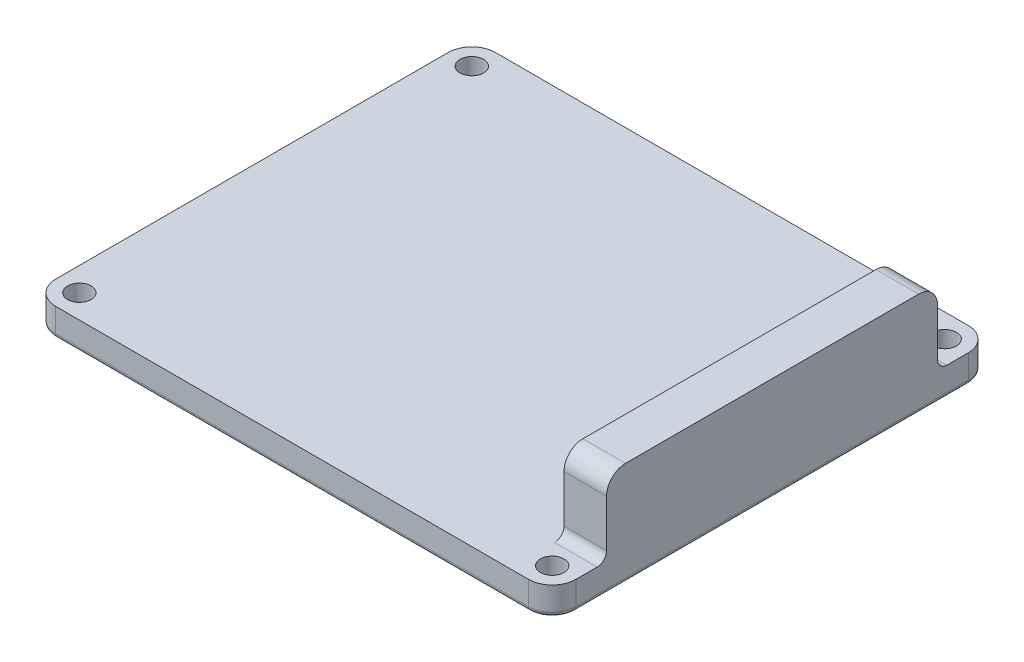
SolidWorks part; units mm, degrees
ref_plane "Front Plane" through (0, 0, 0) normal (0, 0, 1) x (1, 0, 0)
ref_plane "Top Plane" through (0, 0, 0) normal (0, 1, 0) x (1, 0, 0)
ref_plane "Right Plane" through (0, 0, 0) normal (1, 0, 0) x (0, 0, -1)
sketch "Sketch1" plane through (0, 0, 0) normal (0, 1, 0) x (1, 0, 0)
  line L1 (-27.5, -19.25) -> (-27.5, -20.75)
  line L2 (-25, -23.25) -> (25, -23.25)
  line L3 (27.5, -20.75) -> (27.5, 20.75)
  line L4 (25, 23.25) -> (-25, 23.25)
  line L5 (-27.5, 20.75) -> (-27.5, 19.25)
  line L8 (-27.5, 19.25) -> (-27.5, -19.25)
  circle A0 centre (-25, -20.75) radius 1.25
  arc A2 (-27.5, -20.75) -> (-25, -23.25) centre (-25, -20.75) ccw
  arc A3 (25, -23.25) -> (27.5, -20.75) centre (25, -20.75) ccw
  arc A4 (27.5, 20.75) -> (25, 23.25) centre (25, 20.75) ccw
  arc A5 (-25, 23.25) -> (-27.5, 20.75) centre (-25, 20.75) ccw
  circle A9 centre (25, -20.75) radius 1.25
  circle A10 centre (25, 20.75) radius 1.25
  circle A11 centre (-25, 20.75) radius 1.25
extrude "Boss-Extrude1" add sketch "Sketch1" along normal blind 3
sketch "Sketch2" plane through (0, 3, 0) normal (0, 1, 0) x (1, 0, 0)
  line L5 (0, 0) -> (0, 50000) construction
  line L6 (27.5, -17.5) -> (23, -17.5)
  line L7 (23, 17.5) -> (23, -17.5)
  line L8 (27.5, 17.5) -> (23, 17.5)
  line L9 (27.5, 17.5) -> (27.5, -17.5)
  line L10 (27.5, -20.75) -> (27.5, 20.75) construction
  point P0 (27.5, 0)
  dimension "D1" = 35
  dimension "D2" = 4.5
extrude "Boss-Extrude2" add sketch "Sketch2" along normal blind 8
fillet "Fillet1" radius 1 2 edges at (25.25, 3, -17.5) (25.25, 3, 17.5)
fillet "Fillet2" radius 2 2 edges at (25.25, 11, 17.5) (25.25, 11, -17.5)
fillet "Fillet3" radius 0.5 12 edges at (-25, 0, -19.5) (25, 0, -19.5) (25, 0, 22) (-25, 0, 22) (0, 0, 23.25) (26.7678, 0, 22.5178) (27.5, 0, 0) (26.7678, 0, -22.5178) (0, 0, -23.25) (-26.7678, 0, -22.5178) (-27.5, 0, 0) (-26.7678, 0, 22.5178)
